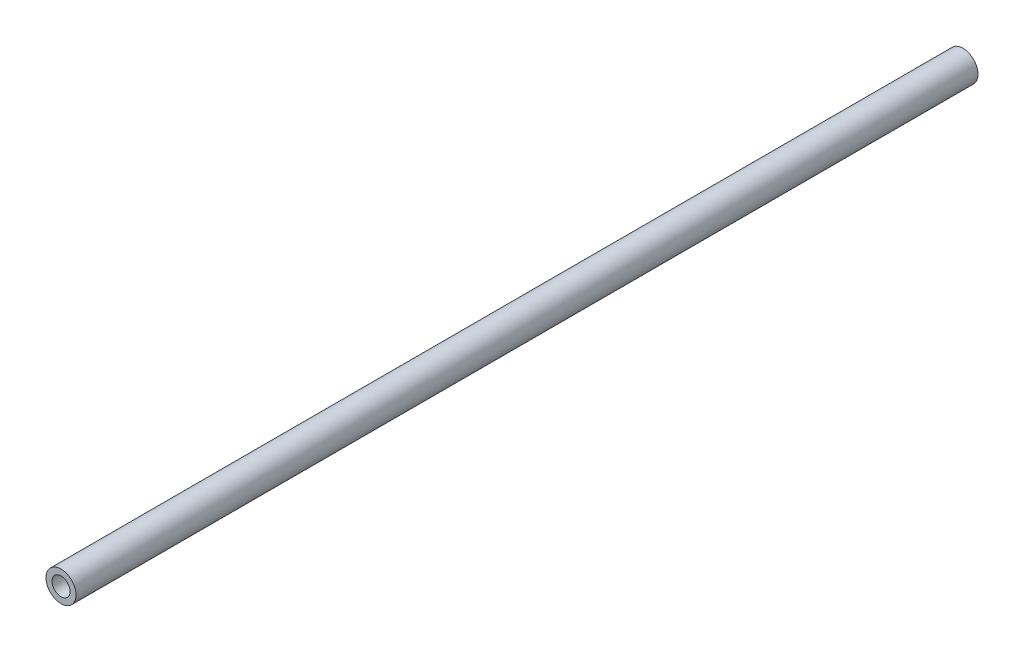
SolidWorks part; units mm, degrees
ref_plane "Plan de face" through (0, 0, 0) normal (0, 0, 1) x (1, 0, 0)
ref_plane "Plan de dessus" through (0, 0, 0) normal (0, 1, 0) x (1, 0, 0)
ref_plane "Plan de droite" through (0, 0, 0) normal (1, 0, 0) x (0, 0, -1)
sketch "Esquisse1" plane through (0, 0, 0) normal (0, 0, 1) x (1, 0, 0)
  circle A0 centre (0, 0) radius 1.5
  circle A1 centre (0, 0) radius 2.5
  dimension "D1" = 3
  dimension "D2" = 5
extrude "Boss.-Extru.1" add sketch "Esquisse1" along normal blind 150
